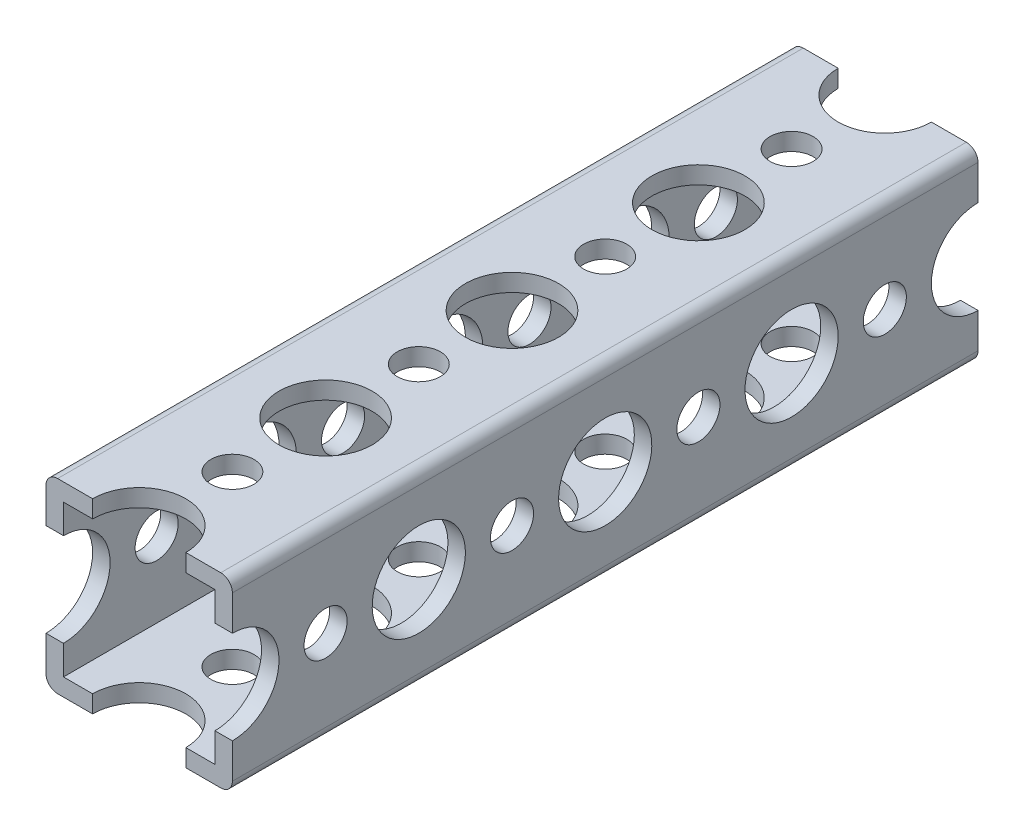
SolidWorks part; units mm, degrees
ref_plane "Front Plane" through (0, 0, 0) normal (0, 0, 1) x (1, 0, 0)
ref_plane "Top Plane" through (0, 0, 0) normal (0, 1, 0) x (1, 0, 0)
ref_plane "Right Plane" through (0, 0, 0) normal (1, 0, 0) x (0, 0, -1)
sketch "Sketch1" plane through (0, 0, 0) normal (0, 0, 1) x (1, 0, 0)
  line L1 (0, 0) -> (16, 0)
  line L2 (0, 0) -> (0, 16)
  line L3 (0, 16) -> (16, 16)
  line L4 (16, 0) -> (16, 16)
  dimension "D1" = 16
  dimension "D2" = 16
extrude "Extrude1" add sketch "Sketch1" against normal blind 64
sketch "Sketch2" plane through (0, 0, 0) normal (0, 0, 1) x (1, 0, 0)
  line L0 (-1.7793, 8) -> (18.8812, 8) construction
  line L1 (8, 16.9255) -> (8, -0.6999) construction
  line L3 (1.5, 14.5) -> (14.5, 14.5)
  line L4 (1.5, 14.5) -> (1.5, 1.5)
  line L5 (1.5, 1.5) -> (14.5, 1.5)
  line L6 (14.5, 14.5) -> (14.5, 1.5)
  line L7 (1.5, 14.5) -> (14.5, 1.5) construction
  line L8 (1.5, 1.5) -> (14.5, 14.5) construction
  point P4 (8, 8)
  dimension "D1" = 13
  dimension "D2" = 13
extrude "Extrude2" cut sketch "Sketch2" against normal through all
sketch "Sketch3" plane through (0, 16, 0) normal (0, 1, 0) x (1, 0, 0)
  line L0 (-10.6019, 48) -> (25.4979, 48) construction
  line L1 (8, -3.3001) -> (8, 305.034) construction
  line L2 (-10.6019, 80) -> (44.8988, 80) construction
  line L4 (16, 0) -> (0, 0) construction
  line L5 (-19.3069, 144) -> (85.0309, 144) construction
  circle A0 centre (8, 64) radius 4
  circle A1 centre (8, 32) radius 4
  circle A3 centre (8, 0) radius 4
  circle A4 centre (8, 96) radius 4
  circle A5 centre (8, 128) radius 4
  circle A6 centre (8, 160) radius 4
  circle A7 centre (8, 192) radius 4
  circle A8 centre (8, 224) radius 4
  circle A9 centre (8, 256) radius 4
  circle B0 centre (8, 48) radius 4
  circle B1 centre (8, 56) radius 1.85
  circle B2 centre (8, 40) radius 1.85
  circle B3 centre (8, 80) radius 4
  circle B4 centre (8, 88) radius 1.85
  circle B5 centre (8, 72) radius 1.85
  circle B6 centre (8, 16) radius 4
  circle B7 centre (8, 24) radius 1.85
  circle B8 centre (8, 8) radius 1.85
  circle B9 centre (8, 112) radius 4
  circle B10 centre (8, 120) radius 1.85
  circle B11 centre (8, 104) radius 1.85
  circle B12 centre (8, 144) radius 4
  circle B13 centre (8, 152) radius 1.85
  circle B14 centre (8, 136) radius 1.85
  circle B15 centre (8, 176) radius 4
  circle B16 centre (8, 184) radius 1.85
  circle B17 centre (8, 168) radius 1.85
  circle B18 centre (8, 208) radius 4
  circle B19 centre (8, 216) radius 1.85
  circle B20 centre (8, 200) radius 1.85
  circle B21 centre (8, 240) radius 4
  circle B22 centre (8, 248) radius 1.85
  circle B23 centre (8, 232) radius 1.85
  dimension "D1" = 24
  dimension "D2" = 16
  dimension "D4" = 16
  dimension "D5" = 32
  dimension "D7" = 16
  dimension "D13" = 48
  dimension "D3" = 24
  dimension "D6" = 64
  dimension "D8" = 48
  dimension "D9" = 32
  dimension "D10" = 64
  dimension "D11" = 96
  dimension "D14" = 16
  dimension "D15" = 80
  dimension "D16" = 112
sketch_block_instance "Block2-1"
sketch_block "Block2"
sketch_block_instance "Block2-4"
sketch_block_instance "Block2-6"
sketch_block_instance "Block2-11"
sketch_block_instance "Block2-12"
sketch_block_instance "Block2-17"
sketch_block_instance "Block2-18"
sketch_block_instance "Block2-19"
extrude "Extrude3" cut sketch "Sketch3" against normal through all
sketch "Sketch4" plane through (16, 0, 0) normal (1, 0, 0) x (0, 0, -1)
  line L0 (-4.9809, 8) -> (308.0277, 8) construction
  line L1 (48, 20.3919) -> (48, -4.2435) construction
  line L2 (0, 0) -> (0, 16) construction
  line L4 (80, -7.5844) -> (80, 23.8371) construction
  line L5 (144, 22.3836) -> (144, -28.3788) construction
  circle A0 centre (32, 8) radius 4
  circle A1 centre (64, 8) radius 4
  circle A2 centre (0, 8) radius 4
  circle A4 centre (96, 8) radius 4
  circle A5 centre (128, 8) radius 4
  circle A6 centre (160, 8) radius 4
  circle A7 centre (192, 8) radius 4
  circle A8 centre (224, 8) radius 4
  circle A9 centre (256, 8) radius 4
  circle B0 centre (48, 8.0742) radius 4
  circle B1 centre (40, 8.0742) radius 1.85
  circle B2 centre (56, 8.0742) radius 1.85
  circle B3 centre (80, 8) radius 4
  circle B4 centre (72, 8) radius 1.85
  circle B5 centre (88, 8) radius 1.85
  circle B6 centre (16, 8) radius 4
  circle B7 centre (8, 8) radius 1.85
  circle B8 centre (24, 8) radius 1.85
  circle B9 centre (112, 8) radius 4
  circle B10 centre (104, 8) radius 1.85
  circle B11 centre (120, 8) radius 1.85
  circle B12 centre (144, 8) radius 4
  circle B13 centre (136, 8) radius 1.85
  circle B14 centre (152, 8) radius 1.85
  circle B15 centre (176, 8) radius 4
  circle B16 centre (168, 8) radius 1.85
  circle B17 centre (184, 8) radius 1.85
  circle B18 centre (208, 8) radius 4
  circle B19 centre (200, 8) radius 1.85
  circle B20 centre (216, 8) radius 1.85
  circle B21 centre (240, 8) radius 4
  circle B22 centre (232, 8) radius 1.85
  circle B23 centre (248, 8) radius 1.85
  dimension "D3" = 16
  dimension "D5" = 32
  dimension "D7" = 16
  dimension "D13" = 16
  dimension "D1" = 24
  dimension "D2" = 24
  dimension "D4" = 16
  dimension "D6" = 64
  dimension "D8" = 48
  dimension "D9" = 32
  dimension "D10" = 64
  dimension "D11" = 96
  dimension "D14" = 48
  dimension "D15" = 80
  dimension "D16" = 112
sketch_block_instance "Block2-8"
sketch_block_instance "Block2-9"
sketch_block_instance "Block2-10"
sketch_block_instance "Block2-14"
sketch_block_instance "Block2-15"
sketch_block_instance "Block2-22"
sketch_block_instance "Block2-23"
sketch_block_instance "Block2-24"
extrude "Extrude4" cut sketch "Sketch4" against normal through all
fillet "Fillet1" radius 1 4 edges at (0, 0, -32) (16, 0, -32) (0, 16, -32) (16, 16, -32)
